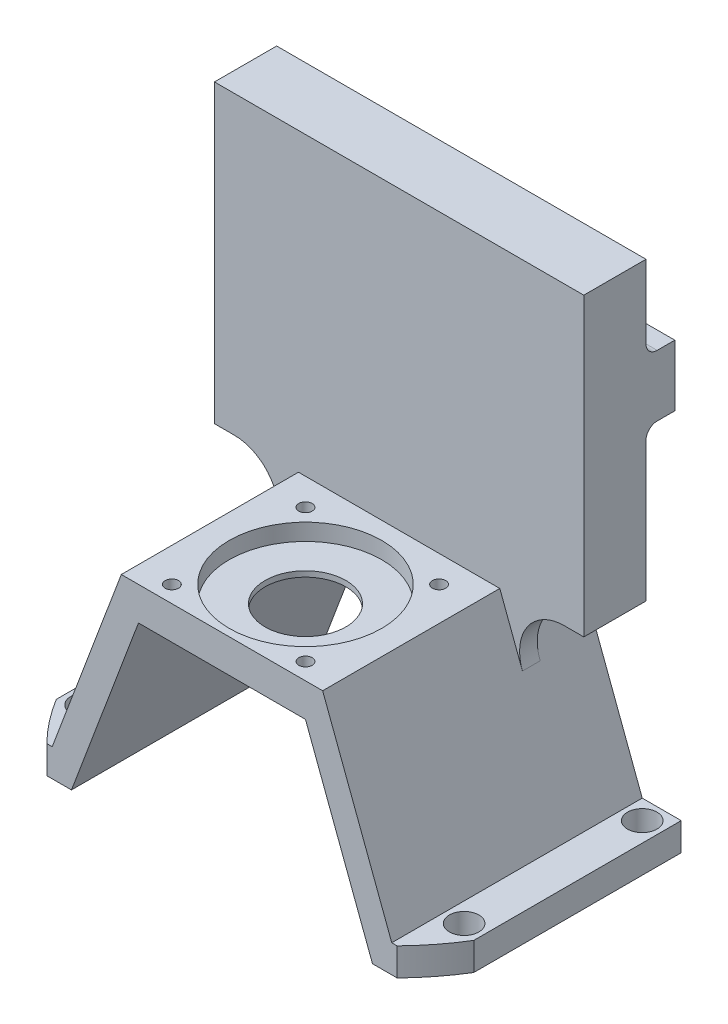
SolidWorks part; units mm, degrees
ref_plane "Front" through (0, 0, 0) normal (0, 0, 1) x (1, 0, 0)
ref_plane "Top" through (0, 0, 0) normal (0, 1, 0) x (1, 0, 0)
ref_plane "Right" through (0, 0, 0) normal (1, 0, 0) x (0, 0, -1)
sketch "Sketch1" plane through (0, 0, 0) normal (0, 0, 1) x (1, 0, 0)
  line L0 (37.5, 0) -> (-37.5, 0) construction
  line L1 (-37.5, 0) -> (-27.0389, 0)
  line L2 (37.5, 0) -> (27.0389, 0)
  line L3 (-37.5, 0) -> (-37.5, 5)
  line L4 (-37.5, 5) -> (-30.5, 5)
  line L5 (-30.5, 5) -> (-18.0848, 38)
  line L6 (-18.0848, 38) -> (18.0848, 38)
  line L7 (18.0848, 38) -> (30.5, 5)
  line L8 (30.5, 5) -> (37.5, 5)
  line L9 (37.5, 5) -> (37.5, 0)
  line L10 (-27.0389, 0) -> (-15, 32)
  line L11 (-15, 32) -> (15, 32)
  line L12 (15, 32) -> (27.0389, 0)
  point P4 (0, 0)
  dimension "D1" = 75
  dimension "D2" = 5
  dimension "D3" = 7
  dimension "D4" = 5
  dimension "D5" = 38
  dimension "D6" = 30
  dimension "D7" = 6
extrude "Boss-Extrude1" add sketch "Sketch1" along normal blind 45
sketch "Sketch2" plane through (0, 38, 0) normal (0, 1, 0) x (1, 0, 0)
  line L0 (0, 0) -> (0, -30) construction
  line L2 (12, -42) -> (-12, -42) construction
  line L3 (12, -42) -> (12, -18) construction
  line L4 (12, -18) -> (-12, -18) construction
  line L5 (-12, -42) -> (-12, -18) construction
  line L6 (12, -42) -> (-12, -18) construction
  line L7 (12, -18) -> (-12, -42) construction
  dimension "D1" = 30
  dimension "D2" = 24
sketch "Sketch3" plane through (0, 38, 0) normal (0, 1, 0) x (1, 0, 0)
  line L0 (12, -18) -> (-12, -42) construction
  circle A0 centre (0, -30) radius 13.7
  dimension "D1" = 27.4
extrude "Cut-Extrude1" cut sketch "Sketch3" against normal blind 3
hole_wizard "CSK for M2 Flat Head Machine Screw1" positions "Sketch5" profile "Sketch6" countersink size "M2" standard "ANSI Metric" end condition through all
sketch "Sketch5" plane through (0, 32, 0) normal (0, -1, 0) x (-1, 0, 0)
  point P0 (12, -42)
  point P3 (-12, -42)
  point P6 (-12, -18)
  point P9 (12, -18)
sketch "Sketch6" plane through (-12, 32, 42) normal (1, 0, 0) x (0, 0, -1)
  line L0 (0, 0) -> (0, 6)
  line L1 (0, 6) -> (1.2, 6)
  line L2 (1.2, 6) -> (1.2, 1)
  line L3 (1.2, 1) -> (2.2, 0)
  line L5 (2.2, 0) -> (0, 0)
  line L6 (-1.2, 1) -> (-2.2, 0) construction
  line L11 (0, -6.35) -> (0, 107.95) construction
  dimension "Thru Hole Dia." = 2.4
  dimension "Thru Hole Depth" = 6
  dimension "Near C'Sink Dia." = 4.4
  dimension "Near C'Sink Angle" = 90
sketch "Sketch10" plane through (0, 35, 0) normal (0, 1, 0) x (1, 0, 0)
  circle A0 centre (0, -30) radius 7.25
  dimension "D1" = 14.5
extrude "Cut-Extrude2" cut sketch "Sketch10" against normal through all
sketch "Sketch15" plane through (0, 38, 0) normal (0, 1, 0) x (1, 0, 0)
  line L0 (0, -30) -> (0, -14.25) construction
  circle A0 centre (0, -14.25) radius 44
  circle A1 centre (0, -14.25) radius 48.4955
  dimension "D2" = 88
  dimension "D1" = 15.75
extrude "Cut-Extrude4" cut sketch "Sketch15" against normal through all
sketch "Sketch11" plane through (0, 32, 0) normal (0, -1, 0) x (1, 0, 0)
  circle A0 centre (0, 30) radius 10.5
  dimension "D1" = 21
extrude "Cut-Extrude3" cut sketch "Sketch11" against normal blind 2
sketch "Sketch7" plane through (0, 0, 0) normal (0, -1, 0) x (1, 0, 0)
  line L0 (0, 19.5) -> (0, 0) construction
  line L1 (-30.5, 35.5) -> (-37.5, 35.5) construction
  line L2 (-34, 3.5) -> (34, 3.5) construction
  line L3 (-34, 3.5) -> (-34, 35.5) construction
  line L4 (-34, 35.5) -> (34, 35.5) construction
  line L5 (34, 3.5) -> (34, 35.5) construction
  line L6 (-34, 3.5) -> (34, 35.5) construction
  line L7 (-34, 35.5) -> (34, 3.5) construction
  line L8 (-30.5, 45) -> (-30.5, 0) construction
  line L9 (-37.5, 37.2663) -> (-37.5, 0) construction
  line L12 (-37.5, 0) -> (-27.0389, 0) construction
  point P4 (0, 19.5)
  point P5 (0, 19.5)
  point P16 (-34, 35.5)
  dimension "D1" = 3.5
  dimension "D2" = 32
hole_wizard "CBORE for M5 Hex Head Bolt1" positions "Sketch13" profile "Sketch14" counterbore size "M5" standard "ANSI Metric" end condition through all
sketch "Sketch13" plane through (0, 5, 0) normal (0, -1, 0) x (-1, 0, 0)
  point P0 (34, -35.5)
  point P3 (34, -3.5)
  point P6 (-34, -3.5)
  point P9 (-34, -35.5)
sketch "Sketch14" plane through (-34, 5, 35.5) normal (1, 0, 0) x (0, 0, 1)
  line L0 (0, 0) -> (0, 5)
  line L1 (0, 5) -> (1.7, 5)
  line L3 (1.7, 5) -> (1.7, 4)
  line L4 (1.7, 4) -> (2.65, 4)
  line L5 (2.65, 4) -> (2.65, 0)
  line L7 (2.65, 0) -> (0, 0)
  line L11 (0, -6.35) -> (0, 107.95) construction
  dimension "Thru Hole Dia." = 3.4
  dimension "Thru Hole Depth" = 5
  dimension "C'Bore Dia." = 5.3
  dimension "C'Bore Depth" = 4
sketch "Sketch19" plane through (0, 38, 0) normal (0, 1, 0) x (1, 0, 0)
  line L0 (18.0848, 0) -> (-18.0848, 0) construction
  line L1 (-33.175, -10) -> (33.175, -10)
  line L2 (-33.175, -10) -> (-33.175, -13.175)
  line L3 (-33.175, -13.175) -> (33.175, -13.175)
  line L4 (33.175, -10) -> (33.175, -13.175)
  point P6 (0, 0)
  point P7 (0, -10)
  dimension "D1" = 3.175
  dimension "D2" = 66.35
  dimension "D3" = 10
extrude "Boss-Extrude5" add sketch "Sketch19" along normal blind 53.175
sketch "Sketch20" plane through (0, 0, 10) normal (0, 0, -1) x (-1, 0, 0)
  line L0 (-33.175, 91.175) -> (33.175, 91.175) construction
  line L2 (30, 38) -> (-30, 38)
  line L3 (30, 38) -> (30, 88)
  line L4 (30, 88) -> (-30, 88)
  line L5 (-30, 38) -> (-30, 88)
  line L6 (-33.175, 38) -> (-18.0848, 38) construction
  point P6 (0, 91.175)
  point P7 (0, 38)
  dimension "D1" = 60
  dimension "D2" = 50
extrude "Boss-Extrude6" [suppressed] add sketch "Sketch20" along normal blind 8
sketch "Sketch21" [suppressed] plane through (0, 0, 2) normal (0, 0, -1) x (-1, 0, 0)
  line L0 (-30, 88) -> (-30, 38) construction
  line L1 (30, 38) -> (-30, 38)
  line L2 (30, 38) -> (30, 63)
  line L3 (30, 63) -> (-30, 63)
  line L4 (-30, 38) -> (-30, 63)
  dimension "D1" = 25
extrude "Boss-Extrude7" [suppressed] add sketch "Sketch21" along normal blind 12
sketch "Sketch22" [suppressed] plane through (0, 0, 2) normal (0, 0, -1) x (-1, 0, 0)
  line L0 (30, 63) -> (30, 88) construction
  line L1 (30, 78) -> (-12, 78)
  line L2 (30, 78) -> (30, 98)
  line L3 (30, 98) -> (-12, 98)
  line L4 (-12, 78) -> (-12, 98)
  line L5 (30, 88) -> (-30, 88) construction
  dimension "D1" = 42
  dimension "D2" = 10
  dimension "D3" = 20
extrude "Boss-Extrude8" [suppressed] add sketch "Sketch22" along normal blind 8
sketch "Sketch23" plane through (0, 0, 10) normal (0, 0, -1) x (-1, 0, 0)
  line L0 (-33.175, 91.175) -> (33.175, 91.175) construction
  line L1 (-33.175, 38) -> (-30, 38)
  line L2 (-33.175, 38) -> (-33.175, 91.175)
  line L3 (-33.175, 91.175) -> (-30, 91.175)
  line L4 (-30, 38) -> (-30, 88)
  line L5 (33.175, 91.175) -> (33.175, 38) construction
  line L6 (-33.175, 91.175) -> (33.175, 91.175)
  line L7 (-33.175, 91.175) -> (-33.175, 38)
  line L8 (-30, 88) -> (33.175, 88)
  line L9 (33.175, 91.175) -> (33.175, 88)
  dimension "D1" = 3.175
extrude "Boss-Extrude9" add sketch "Sketch23" along normal blind 8
fillet "Fillet2" radius 8 1 edges at (18.0848, 38, 11.5875)
fillet "Fillet3" radius 8 1 edges at (-18.0848, 38, 11.5875)
sketch "Sketch24" plane through (0, 0, 2) normal (0, 0, -1) x (-1, 0, 0)
  line L0 (-30, 38) -> (-30, 88) construction
  line L1 (-30, 65) -> (-33.175, 65)
  line L2 (-30, 65) -> (-30, 76)
  line L3 (-30, 76) -> (-33.175, 76)
  line L4 (-33.175, 65) -> (-33.175, 76)
  line L5 (-33.175, 91.175) -> (-33.175, 38) construction
  line L6 (-33.175, 38) -> (-30, 38) construction
  line L7 (33.175, 91.175) -> (-33.175, 91.175) construction
  dimension "D1" = 27
  dimension "D2" = 15.175
extrude "Boss-Extrude10" add sketch "Sketch24" along normal blind 5.175
sketch "Sketch25" plane through (30, 0, 0) normal (-1, 0, 0) x (0, 0, 1)
  line L0 (-3.175, 76) -> (2, 76) construction
  line L1 (-3.175, 65) -> (0, 65)
  line L2 (-3.175, 65) -> (-3.175, 76)
  line L3 (-3.175, 76) -> (0, 76)
  line L4 (0, 65) -> (0, 76)
  dimension "D1" = 3.175
extrude "Boss-Extrude11" add sketch "Sketch25" along normal blind 60
fillet "Fillet4" radius 2 2 edges at (31.5875, 76, 2) (31.5875, 65, 2)
